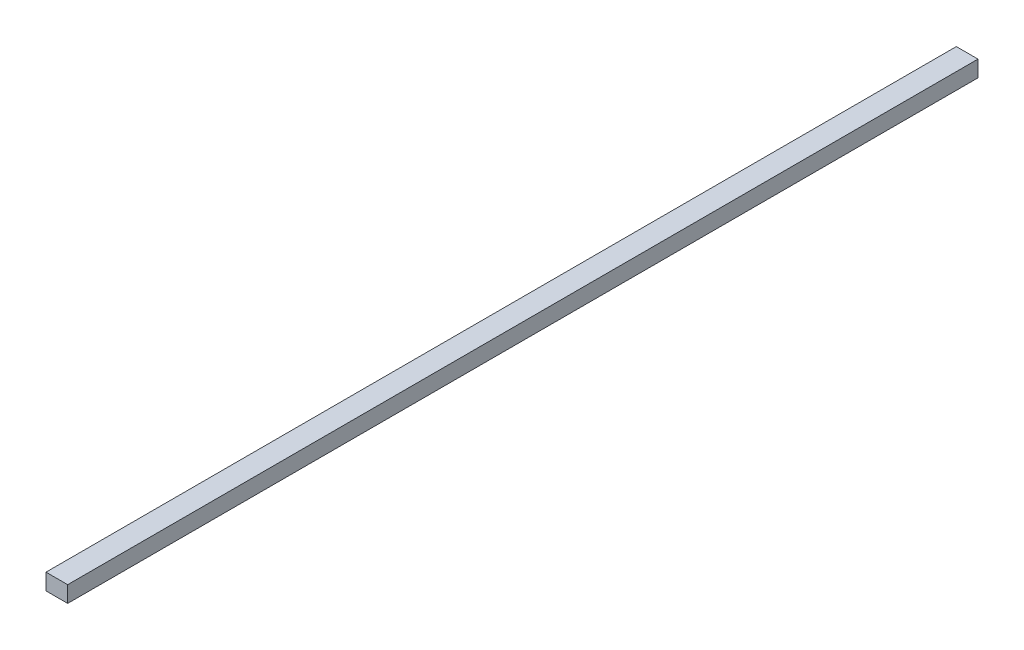
SolidWorks part; units mm, degrees
ref_plane "Front Plane" through (0, 0, 0) normal (0, 0, 1) x (1, 0, 0)
ref_plane "Top Plane" through (0, 0, 0) normal (0, 1, 0) x (1, 0, 0)
ref_plane "Right Plane" through (0, 0, 0) normal (1, 0, 0) x (0, 0, -1)
sketch "Sketch1" plane through (0, 0, 0) normal (0, 1, 0) x (1, 0, 0)
  line L1 (-12.7, -533.4) -> (12.7, -533.4)
  line L2 (-12.7, -533.4) -> (-12.7, 533.4)
  line L3 (-12.7, 533.4) -> (12.7, 533.4)
  line L4 (12.7, -533.4) -> (12.7, 533.4)
  line L5 (-12.7, -533.4) -> (12.7, 533.4) construction
  line L6 (-12.7, 533.4) -> (12.7, -533.4) construction
  point P0 (0, 0)
  dimension "D1" = 1066.8
  dimension "D2" = 25.4
extrude "Boss-Extrude1" add sketch "Sketch1" along normal blind 19.05
